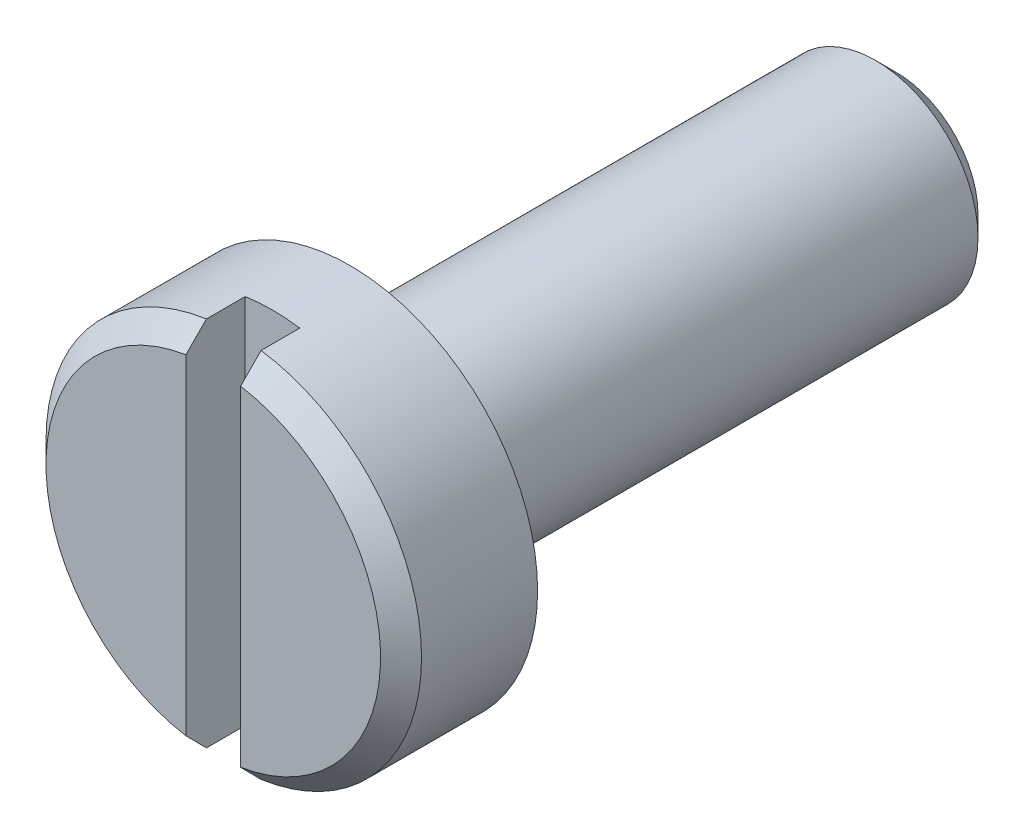
SolidWorks part; units mm, degrees
ref_plane "Front Plane" through (0, 0, 0) normal (0, 0, 1) x (1, 0, 0)
ref_plane "Top Plane" through (0, 0, 0) normal (0, 1, 0) x (1, 0, 0)
ref_plane "Right Plane" through (0, 0, 0) normal (1, 0, 0) x (0, 0, -1)
sketch "Sketch1" plane through (0, 0, 0) normal (0, 0, 1) x (1, 0, 0)
  circle A0 centre (0, 0) radius 1.5
extrude "Boss-Extrude1" add sketch "Sketch1" against normal blind 8
sketch "Sketch2" plane through (0, 0, 0) normal (0, 0, 1) x (1, 0, 0)
  circle A0 centre (0, 0) radius 2.75
extrude "Boss-Extrude2" add sketch "Sketch2" along normal blind 2
chamfer "Chamfer1" distance 0.3 angle 45 2 edges at (1.5, 0, -8) (2.75, 0, 2)
sketch "Sketch3" plane through (0, 0, 0) normal (0, 1, 0) x (1, 0, 0)
  line L5 (0.4, -2.8327) -> (0.4, -1.1327)
  line L6 (0.4, -2.8327) -> (-0.4, -2.8327)
  line L7 (0.4, -1.1327) -> (-0.4, -1.1327)
  line L8 (-0.4, -2.8327) -> (-0.4, -1.1327)
  line L9 (0.4, -2.8327) -> (-0.4, -1.1327) construction
  line L10 (0.4, -1.1327) -> (-0.4, -2.8327) construction
  line L11 (0, 0) -> (0, 0.9451) construction
  point P1 (0, -1.9827)
  dimension "D1" = 0.85
  dimension "D2" = 0.8
extrude "Cut-Extrude1" cut sketch "Sketch3" against normal through all both and the other way through all
